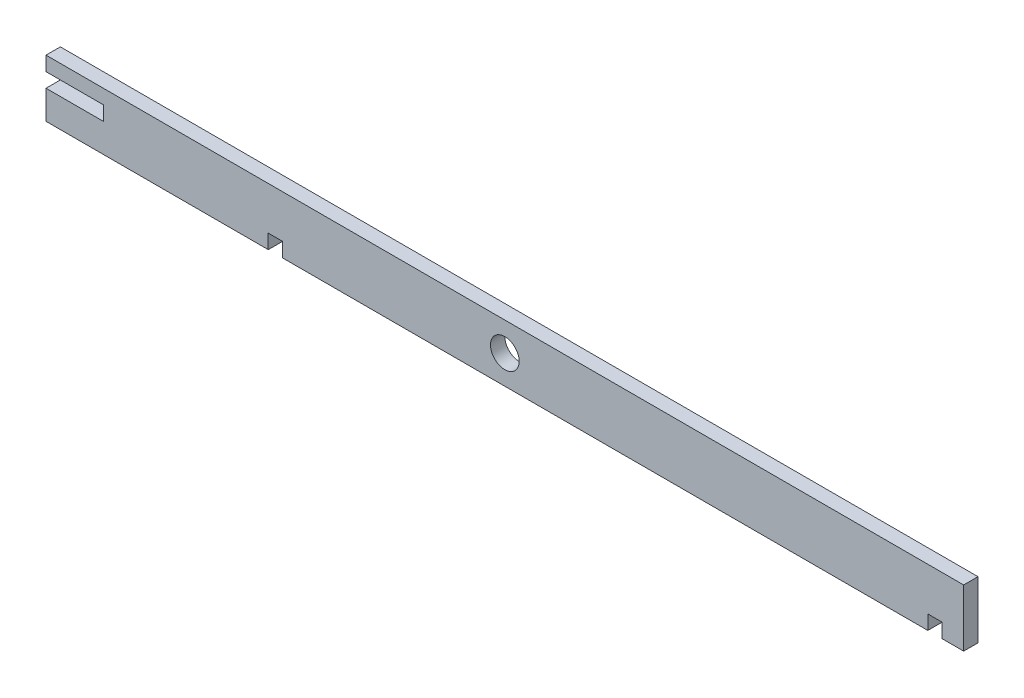
SolidWorks part; units mm, degrees
ref_plane "Front Plane" through (0, 0, 0) normal (0, 0, 1) x (1, 0, 0)
ref_plane "Top Plane" through (0, 0, 0) normal (0, 1, 0) x (1, 0, 0)
ref_plane "Right Plane" through (0, 0, 0) normal (1, 0, 0) x (0, 0, -1)
sketch "Sketch2" plane through (0, 0, 0) normal (0, 0, 1) x (1, 0, 0)
  line L0 (0, 0) -> (-203.2, 0)
  line L1 (-203.2, 0) -> (-203.2, -12.7)
  line L2 (-203.2, -12.7) -> (0, -12.7)
  line L3 (0, -12.7) -> (0, 0)
  line L4 (0, -6.35) -> (-6.35, -6.35) construction
  line L5 (-6.35, -6.35) -> (-6.35, -9.525) construction
  line L6 (-7.9375, -9.525) -> (-4.7625, -9.525)
  line L7 (-4.7625, -9.525) -> (-4.7625, -12.7)
  line L8 (-7.9375, -9.525) -> (-7.9375, -12.7)
  line L9 (-101.6, 0) -> (-101.6, -6.35) construction
  line L10 (0, -6.35) -> (-101.6, -6.35) construction
  line L11 (-203.2, -6.35) -> (-190.5, -6.35)
  line L12 (-190.5, -6.35) -> (-190.5, -3.175)
  line L13 (-190.5, -3.175) -> (-203.2, -3.175)
  line L14 (-101.6, -6.35) -> (-152.4, -6.35) construction
  line L15 (-152.4, -6.35) -> (-152.4, -9.525) construction
  line L16 (-153.9875, -9.525) -> (-150.8125, -9.525)
  line L17 (-150.8125, -9.525) -> (-150.8125, -12.7)
  line L18 (-153.9875, -9.525) -> (-153.9875, -12.7)
  circle A0 centre (-101.6, -6.35) radius 3.175
  point P12 (-6.35, -9.525)
  point P24 (-152.4, -9.525)
  dimension "D6" = 6.35
  dimension "D1" = 203.2
  dimension "D2" = 12.7
  dimension "D3" = 6.35
  dimension "D4" = 3.175
  dimension "D5" = 3.175
  dimension "D7" = 12.7
  dimension "D8" = 3.175
  dimension "D9" = 50.8
  dimension "D10" = 3.175
extrude "Boss-Extrude1" add sketch "Sketch2" along normal blind 3.175 contours L18 L16 L17 L2 L8 L6 L7 L3 L0 L1 L13 L12 L11 A0
